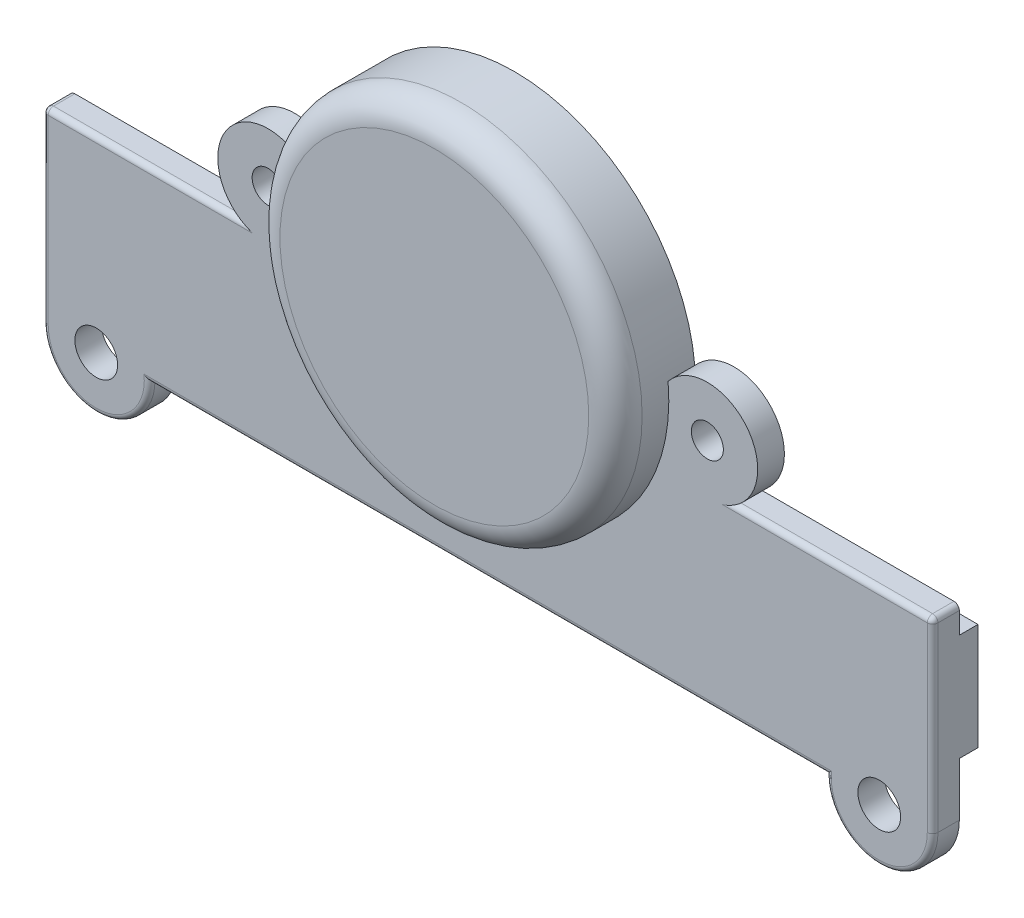
SolidWorks part; units mm, degrees
ref_plane "Front Plane" through (0, 0, 0) normal (0, 0, 1) x (1, 0, 0)
ref_plane "Top Plane" through (0, 0, 0) normal (0, 1, 0) x (1, 0, 0)
ref_plane "Right Plane" through (0, 0, 0) normal (1, 0, 0) x (0, 0, -1)
sketch "Sketch1" plane through (0, 0, 0) normal (0, 0, 1) x (1, 0, 0)
  line L1 (-83.3333, -35.8592) -> (-83.3333, -10.8592)
  line L2 (83.3333, -35.8592) -> (83.3333, -10.8592)
  line L3 (-83.3333, -10.8592) -> (-46.1356, -10.8592)
  line L4 (83.3333, -10.8592) -> (46.1356, -10.8592)
  line L5 (-83.3333, -35.8592) -> (-83.3333, -45.8592)
  line L6 (-63.3333, -45.8592) -> (0, -45.8592)
  line L7 (83.3333, -35.8592) -> (83.3333, -45.8592)
  line L8 (0, -45.8592) -> (63.3333, -45.8592)
  circle A0 centre (0, 0) radius 14
  arc A1 (33.7832, 3.052) -> (-33.7832, 3.052) centre (0, 0) ccw
  circle A6 centre (-73.3333, -45.8592) radius 4
  circle A7 centre (73.3333, -45.8592) radius 4
  arc A9 (-83.3333, -45.8592) -> (-63.3333, -45.8592) centre (-73.3333, -45.8592) ccw
  arc A10 (63.3333, -45.8592) -> (83.3333, -45.8592) centre (73.3333, -45.8592) ccw
  circle A13 centre (-41.1356, -2.8592) radius 3
  circle A14 centre (41.1356, -2.8592) radius 3
  arc A15 (-33.7832, 3.052) -> (-46.1356, -10.8592) centre (-41.1356, -2.8592) ccw
  arc A16 (46.1356, -10.8592) -> (33.7832, 3.052) centre (41.1356, -2.8592) ccw
  point P9 (-32.1356, -10.8592)
  point P10 (32.1356, -10.8592)
  dimension "D1" = 28
  dimension "D2" = 67.8416
  dimension "D7" = 8
  dimension "D8" = 8
  dimension "D16" = 6
  dimension "D17" = 6
  dimension "D4" = 83.3333
  dimension "D5" = 83.3333
  dimension "D11" = 10
  dimension "D12" = 10
  dimension "D13" = 10
  dimension "D14" = 10
  dimension "D6" = 35.8592
  dimension "D10" = 35
  dimension "D19" = 8
  dimension "D18" = 5
  dimension "D20" = 5
  dimension "D22" = 10
  dimension "D15" = 9
extrude "Boss-Extrude2" add sketch "Sketch1" along normal blind 5
sketch "Sketch2" plane through (0, 0, 5) normal (0, 0, 1) x (1, 0, 0)
  circle A0 centre (0, 0) radius 33.9208
  arc A1 (33.7832, 3.052) -> (-33.7832, 3.052) centre (0, 0) ccw construction
extrude "Boss-Extrude3" add sketch "Sketch2" along normal blind 10
sketch "Sketch3" plane through (0, 0, 0) normal (0, 0, -1) x (-1, 0, 0)
  line L0 (-83.3333, -10.8592) -> (-83.3333, -45.8592) construction
  line L1 (-83.3333, -35.8592) -> (83.3333, -35.8592)
  line L2 (-83.3333, -35.8592) -> (-83.3333, -15.8592)
  line L3 (-83.3333, -15.8592) -> (-5.2297, -15.8592)
  line L4 (83.3333, -35.8592) -> (83.3333, -15.8592)
  line L5 (83.3333, -45.8592) -> (83.3333, -10.8592) construction
  line L6 (-5.2297, -15.8592) -> (83.3333, -15.8592)
  line L8 (-83.3333, -10.8592) -> (-46.1356, -10.8592) construction
  dimension "D1" = 35.8592
  dimension "D2" = 5
extrude "Boss-Extrude4" add sketch "Sketch3" along normal blind 3.5
sketch "Sketch5" plane through (0, 0, 5) normal (0, 0, -1) x (-1, 0, 0)
  circle A0 centre (0, 0) radius 14
  circle A1 centre (0, 0) radius 14 construction
extrude "Cut-Extrude1" cut sketch "Sketch5" against normal blind 2
fillet "Fillet1" radius 5 1 edges at (33.9208, 0, 15)
sketch "Sketch6" plane through (0, 0, 7) normal (0, 0, -1) x (-1, 0, 0)
  circle A0 centre (0, 0) radius 12
  dimension "D1" = 24
extrude "Cut-Extrude2" cut sketch "Sketch6" against normal blind 5
fillet "Fillet2" radius 1 9 edges at (-83.3333, -10.8592, 2.5) (83.3333, -10.8592, 2.5) (-83.3333, -28.3592, 5) (-73.3333, -55.8592, 5) (73.3333, -55.8592, 5) (83.3333, -28.3592, 5) (0, -45.8592, 5) (-64.7345, -10.8592, 5) (64.7345, -10.8592, 5)
equation "\"column angle\" = 45deg "
equation "\"short_bearing_outer_width\" = 10mm "
equation "\"wheel base\" = 1561mm "
equation "\"track\" = 1354mm "
equation "\"turning radius\" = 2000mm "
equation "\"turn to lock\" = 0.75mm "
equation "\"steering arm length\" = 100mm "
equation "\"primary shaft small diameter\" = 16mm "
equation "\"primary shaft large diameter\" = 24mm "
equation "\"secondary shaft small diameter\" = 16mm "
equation "\"secondary shaft large diameter\" = 25mm "
equation "\"steering column length\" = 555mm "
equation "\"keyway_height\" = 1.39mm "
equation "\"keyway_width\" = 2.78mm "
equation "\"keyway_length\" = 30mm "
equation "\"steering wheel bolt width\" = 6mm "
equation "\"steering wheel bolt length\" = 40mm "
equation "\"bushing length\" = 40mm "
equation "\"bushing thickness\" = 3mm "
equation "\"u_joint clearance\" = 30mm "
equation "\"u_joint thickness\" = 7.5mm "
equation "\"horizontal shaft length\" = 90mm "
equation "\"column bushing diameter\" = \"primary shaft small diameter\" + 4 "
equation "\"column bushing distance\" = \"steering column length\"/4 "
equation "\"pinion width\" = 26.5mm "
equation "\"pin hole diameter\" = 10mm "
equation "\"rack hole to hole\" = 500mm "
equation "\"rack length\" = \"rack hole to hole\" + \"pin hole diameter\"*2 "
equation "\"max turning angle\" = atn(\"wheel base\" / (\"turning radius\" - 0.5 * \"track\")) "
equation "\"max travel\" = 2 * \"steering arm length\" * sin(0.5 * \"max turning angle\") "
equation "\"pitch diameter\" = \"max travel\"/(pi * \"turn to lock\") "
equation "\"number of teeth\" = 18mm "
equation "\"pressure angle\" = 20deg "
equation "\"module\" = \"pitch diameter\" / \"number of teeth\" "
equation "\"tie rod length\" = 305mm "
equation "\"tie rod inner diameter\" = 6.6mm "
equation "\"tie rod outer diameter\" = 8.1mm "
equation "\"D2@Sketch1\"=\"secondary shaft large diameter\"*2+\"pitch diameter\"/2"
equation "\"D4@Sketch1\"=\"rack hole to hole\"/6"
equation "\"D5@Sketch1\"=\"rack hole to hole\"/6"
equation "\"D6@Sketch1\"=\"pitch diameter\"/2+20-\"module\""
equation "\"D1@Sketch3\"=\"pitch diameter\"/2 + 20-\"module\""
equation "\"D1@Sketch6\"=\"secondary shaft small diameter\"*1.5"
